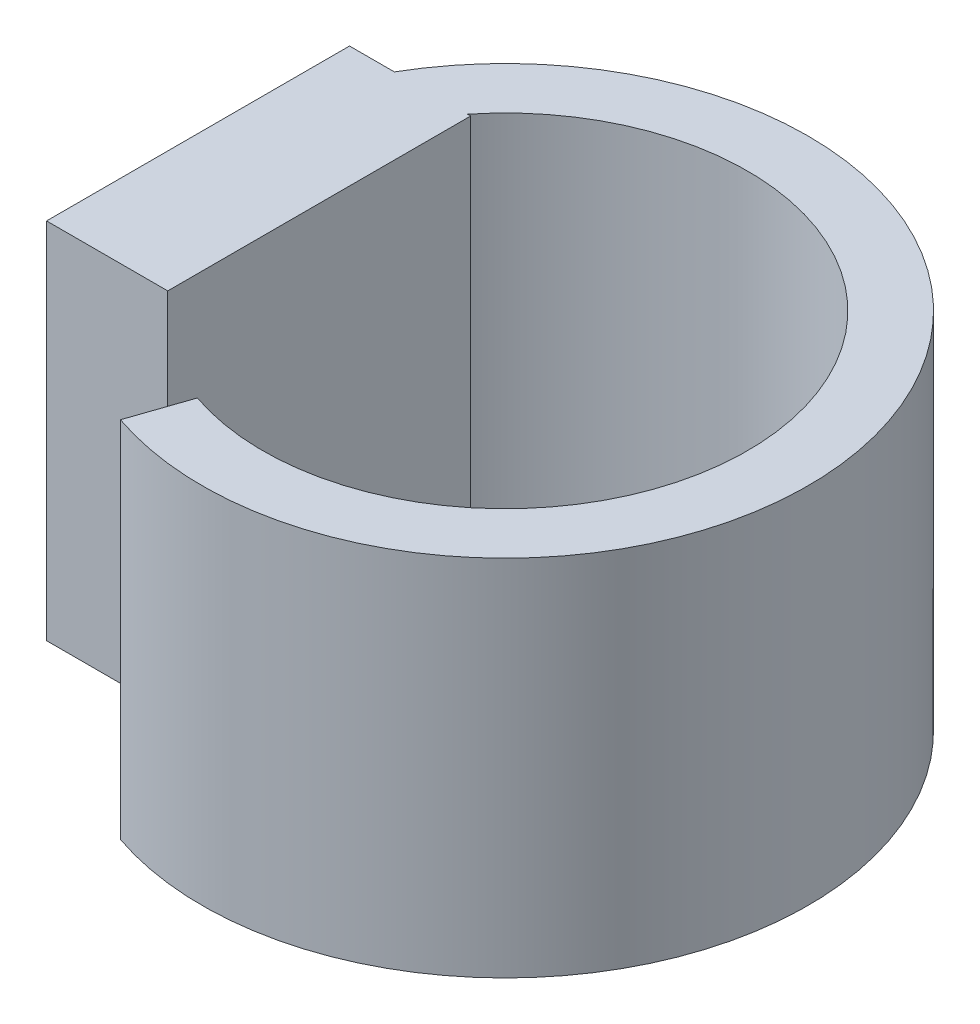
SolidWorks part; units mm, degrees
ref_plane "Front Plane" through (0, 0, 0) normal (0, 0, 1) x (1, 0, 0)
ref_plane "Top Plane" through (0, 0, 0) normal (0, 1, 0) x (1, 0, 0)
ref_plane "Right Plane" through (0, 0, 0) normal (1, 0, 0) x (0, 0, -1)
sketch "Sketch1" plane through (0, 0, 0) normal (0, 1, 0) x (1, 0, 0)
  line L0 (7.5503, -2.5723) -> (6.9031, -4.4647)
  line L1 (0, 0) -> (4, 0)
  line L2 (0, 0) -> (0, 10)
  line L3 (0, 10) -> (1.4803, 10)
  line L4 (4, 0) -> (4, 10)
  line L5 (3.8962, 10) -> (4, 10)
  arc A0 (7.5503, -2.5723) -> (3.8962, 10) centre (10.139, 4.9972) ccw
  arc A1 (6.9031, -4.4647) -> (1.4803, 10) centre (10.139, 4.9972) ccw
  circle A2 centre (10.139, 4.9972) radius 10 construction
  circle A3 centre (10.139, 4.9972) radius 8 construction
  dimension "D1" = 2
extrude "Boss-Extrude1" add sketch "Sketch1" along normal blind 12
